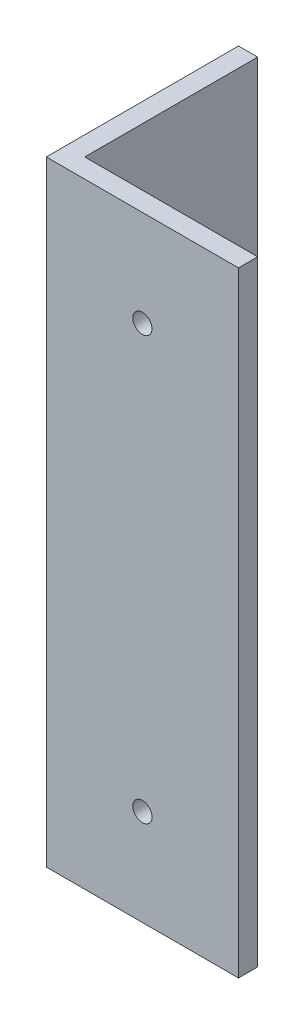
SolidWorks part; units mm, degrees
material "Plain Carbon Steel"
ref_plane "Front Plane" through (0, 0, 0) normal (0, 0, 1) x (1, 0, 0)
ref_plane "Top Plane" through (0, 0, 0) normal (0, 1, 0) x (1, 0, 0)
ref_plane "Right Plane" through (0, 0, 0) normal (1, 0, 0) x (0, 0, -1)
sketch "Sketch1" plane through (0, 0, 0) normal (0, 1, 0) x (1, 0, 0)
  line L0 (0, 0) -> (0, 50)
  line L1 (0, 50) -> (5, 50)
  line L2 (5, 50) -> (5, 5)
  line L3 (5, 5) -> (50, 5)
  line L4 (50, 5) -> (50, 0)
  line L5 (50, 0) -> (0, 0)
  line L6 (0, 0) -> (5, 5) construction
  dimension "D1" = 50
  dimension "D2" = 5
extrude "Boss-Extrude1" add sketch "Sketch1" along normal mid plane 160
sketch "Sketch2" plane through (0, 0, 0) normal (0, 0, 1) x (1, 0, 0)
  line L0 (0, 80) -> (50, 80) construction
  line L1 (0, 0) -> (-34.0332, 0) construction
  circle A0 centre (25, 55) radius 2.5
  circle A1 centre (25, -55) radius 2.5
  point P4 (25, 80)
  point P10 (0, 0)
  dimension "D1" = 5
  dimension "D2" = 25
extrude "Cut-Extrude1" cut sketch "Sketch2" against normal through all
sketch "Sketch3" plane through (0, 0, 0) normal (-1, 0, 0) x (0, 0, 1)
  line L1 (0, 0) -> (-63.5874, 0) construction
  line L2 (-50, 80) -> (0, 80) construction
  line L3 (0, 80) -> (0, -80) construction
  circle A0 centre (-25, 55) radius 2.5
  circle A1 centre (-25, -55) radius 2.5
  point P2 (0, 0)
  point P10 (-4.5542, 51.6345)
  point P11 (0, 0)
  point P12 (-29.5542, 52.1467)
  point P15 (-25, 80)
  dimension "D1" = 5
extrude "Cut-Extrude2" cut sketch "Sketch3" against normal through all
